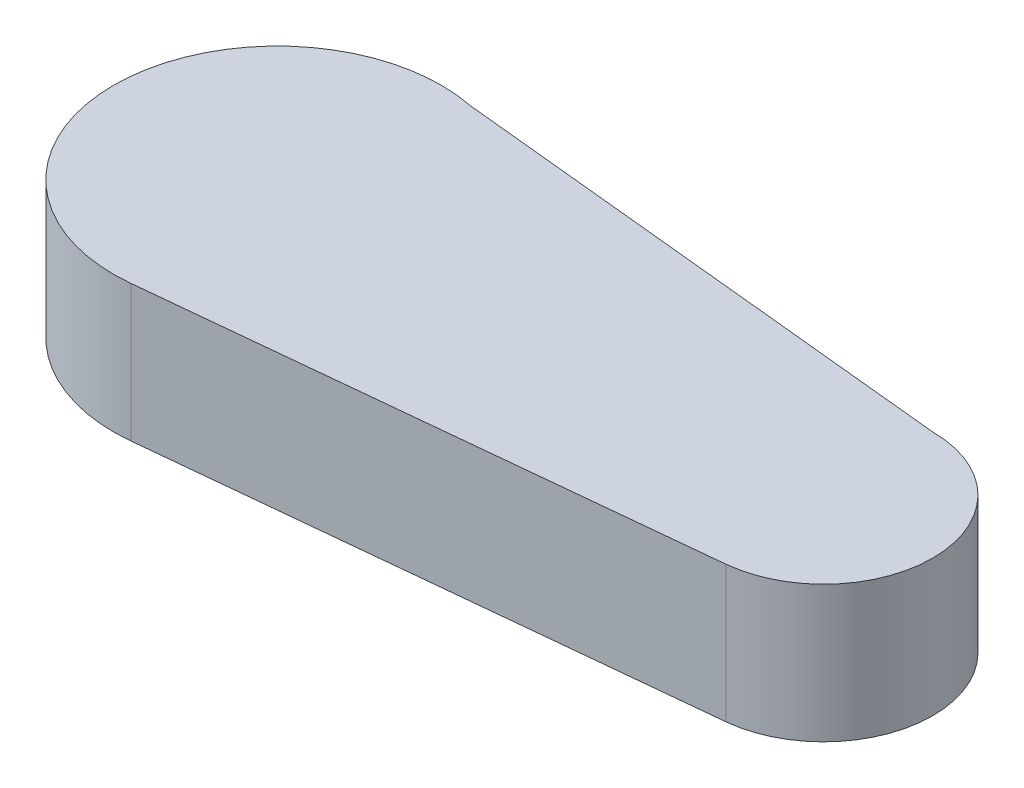
SolidWorks part; units mm, degrees
ref_plane "Front Plane" through (0, 0, 0) normal (0, 0, 1) x (1, 0, 0)
ref_plane "Top Plane" through (0, 0, 0) normal (0, 1, 0) x (1, 0, 0)
ref_plane "Right Plane" through (0, 0, 0) normal (1, 0, 0) x (0, 0, -1)
sketch "Sketch3" plane through (0, 0, 0) normal (0, 1, 0) x (1, 0, 0)
  line L0 (0, 0) -> (-74.221, 0) construction
  line L1 (0, 0) -> (110.7649, 0) construction
  line L2 (-47.3088, 46.4589) -> (-47.3088, -56.6572) construction
  line L3 (52.6912, 46.4589) -> (52.6912, -56.6572) construction
  line L4 (-41.3682, 29.4059) -> (52.6912, 20)
  line L5 (-44.3088, -29.8496) -> (54.6912, -19.8997)
  arc A0 (-41.3682, 29.4059) -> (-44.3088, -29.8496) centre (-47.3088, 0) ccw
  arc A1 (54.6912, -19.8997) -> (52.6912, 20) centre (52.6912, 0) ccw
  dimension "D2" = 60
  dimension "D3" = 40
  dimension "D1" = 100
extrude "Boss-Extrude1" add sketch "Sketch3" along normal blind 25
